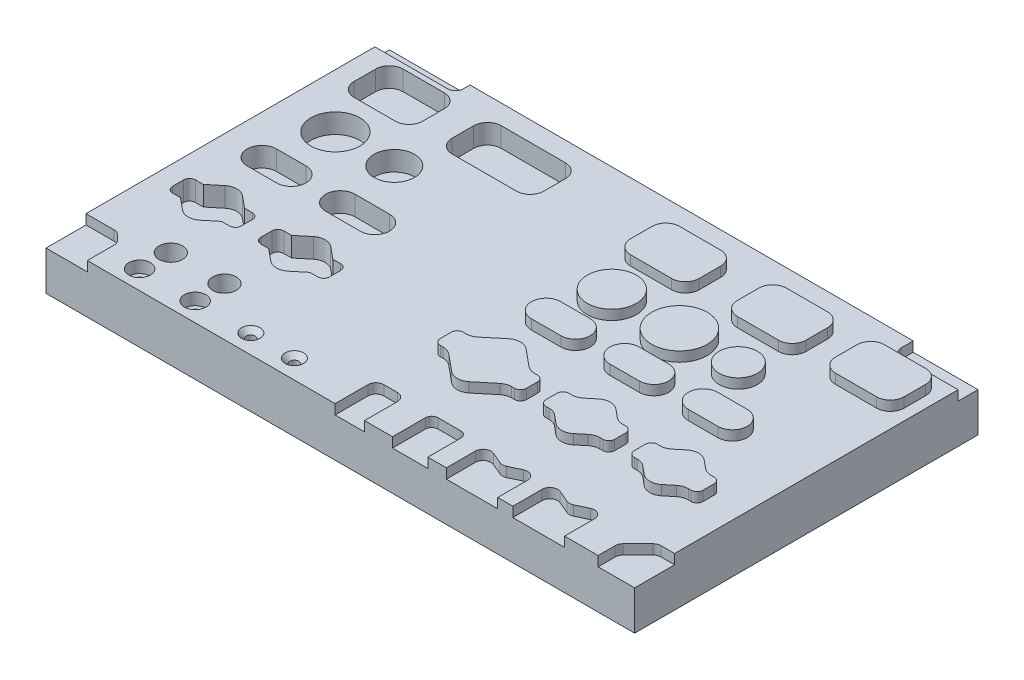
SolidWorks part; units mm, degrees
ref_plane "Front Plane" through (0, 0, 0) normal (0, 0, 1) x (1, 0, 0)
ref_plane "Top Plane" through (0, 0, 0) normal (0, 1, 0) x (1, 0, 0)
ref_plane "Right Plane" through (0, 0, 0) normal (1, 0, 0) x (0, 0, -1)
sketch "Sketch1" plane through (0, 0, 0) normal (0, 1, 0) x (1, 0, 0)
  line L1 (0, 0) -> (300, 0)
  line L2 (0, 0) -> (0, 175)
  line L3 (0, 175) -> (300, 175)
  line L4 (300, 0) -> (300, 175)
  dimension "D1" = 300
  dimension "D2" = 175
extrude "Boss-Extrude1" add sketch "Sketch1" against normal blind 25
sketch "Sketch2" plane through (0, 0, 0) normal (0, 1, 0) x (1, 0, 0)
  line L0 (0, 175) -> (0, 0) construction
  line L1 (27, 140) -> (48, 140)
  line L2 (20, 147) -> (20, 158)
  line L3 (27, 165) -> (48, 165)
  line L4 (55, 147) -> (55, 158)
  line L5 (300, 175) -> (0, 175) construction
  line L6 (89.9746, 138.8199) -> (122.7352, 138.8199)
  line L7 (82.9746, 145.8199) -> (82.9746, 156.8199)
  line L8 (89.9746, 163.8199) -> (122.7352, 163.8199)
  line L9 (129.7352, 145.8199) -> (129.7352, 156.8199)
  line L14 (37.5, 140) -> (37.5, 55.1696) construction
  line L15 (30, 90) -> (45, 90) construction
  line L16 (30, 97.5) -> (45, 97.5)
  line L17 (30, 82.5) -> (45, 82.5)
  line L18 (60, 90) -> (77.5906, 90) construction
  line L19 (60, 97.5) -> (77.5906, 97.5)
  line L20 (60, 82.5) -> (77.5906, 82.5)
  line L24 (33.0424, 76.426) -> (17, 63.1763)
  line L25 (17, 63.1763) -> (13, 63.1763)
  line L26 (10, 60.1763) -> (10, 54.5137)
  line L27 (10, 57.345) -> (37.5, 57.345) construction
  line L28 (65, 60.1763) -> (65, 54.5137)
  line L29 (58, 63.1763) -> (62, 63.1763)
  line L30 (41.9576, 76.426) -> (58, 63.1763)
  line L31 (41.9576, 38.2639) -> (58, 51.5137)
  line L32 (58, 51.5137) -> (62, 51.5137)
  line L33 (17, 51.5137) -> (13, 51.5137)
  line L34 (33.0424, 38.2639) -> (17, 51.5137)
  line L35 (68.0424, 68.1668) -> (62, 63.1763)
  line L36 (62, 63.1763) -> (58, 63.1763)
  line L37 (55, 60.1763) -> (55, 54.5137)
  line L38 (90, 60.1763) -> (90, 54.5137)
  line L39 (83, 63.1763) -> (87, 63.1763)
  line L40 (76.9576, 68.1668) -> (83, 63.1763)
  line L41 (76.9576, 46.5231) -> (83, 51.5137)
  line L42 (83, 51.5137) -> (87, 51.5137)
  line L43 (62, 51.5137) -> (58, 51.5137)
  line L44 (68.0424, 46.5231) -> (62, 51.5137)
  line L45 (55, 57.345) -> (72.5, 57.345) construction
  line L57 (161.8786, 135.9976) -> (182.8786, 135.9976)
  line L58 (154.8786, 142.9976) -> (154.8786, 153.9976)
  line L59 (161.8786, 160.9976) -> (182.8786, 160.9976)
  line L60 (189.8786, 142.9976) -> (189.8786, 153.9976)
  line L61 (216.3363, 135.9976) -> (237.3363, 135.9976)
  line L62 (209.3363, 142.9976) -> (209.3363, 153.9976)
  line L63 (216.3363, 160.9976) -> (237.3363, 160.9976)
  line L64 (244.3363, 142.9976) -> (244.3363, 153.9976)
  line L65 (266.3363, 135.9976) -> (287.3363, 135.9976)
  line L66 (259.3363, 142.9976) -> (259.3363, 153.9976)
  line L67 (266.3363, 160.9976) -> (287.3363, 160.9976)
  line L68 (294.3363, 142.9976) -> (294.3363, 153.9976)
  line L69 (172.3786, 135.9976) -> (172.3786, 51.1671) construction
  line L70 (164.8786, 90) -> (179.8786, 90) construction
  line L71 (164.8786, 97.5) -> (179.8786, 97.5)
  line L72 (164.8786, 82.5) -> (179.8786, 82.5)
  line L73 (204.8786, 90) -> (219.8786, 90) construction
  line L74 (204.8786, 97.5) -> (219.8786, 97.5)
  line L75 (204.8786, 82.5) -> (219.8786, 82.5)
  line L76 (244.8786, 90) -> (259.8786, 90) construction
  line L77 (244.8786, 97.5) -> (259.8786, 97.5)
  line L78 (244.8786, 82.5) -> (259.8786, 82.5)
  line L79 (167.921, 67.846) -> (157.421, 59.1738)
  line L80 (157.421, 59.1738) -> (153.421, 59.1738)
  line L81 (150.421, 56.1738) -> (150.421, 50.5112)
  line L82 (150.421, 53.3425) -> (172.3786, 53.3425) construction
  line L83 (194.3363, 56.1738) -> (194.3363, 50.5112)
  line L84 (187.3363, 59.1738) -> (191.3363, 59.1738)
  line L85 (176.8363, 67.846) -> (187.3363, 59.1738)
  line L86 (176.8363, 38.839) -> (187.3363, 47.5112)
  line L87 (187.3363, 47.5112) -> (191.3363, 47.5112)
  line L88 (157.421, 47.5112) -> (153.421, 47.5112)
  line L89 (167.921, 38.839) -> (157.421, 47.5112)
  line L90 (217.3786, 64.1644) -> (211.3363, 59.1738)
  line L91 (211.3363, 59.1738) -> (207.3363, 59.1738)
  line L92 (204.3363, 56.1738) -> (204.3363, 50.5112)
  line L93 (239.3363, 56.1738) -> (239.3363, 50.5112)
  line L94 (232.3363, 59.1738) -> (236.3363, 59.1738)
  line L95 (226.2939, 64.1644) -> (232.3363, 59.1738)
  line L96 (226.2939, 42.5207) -> (232.3363, 47.5112)
  line L97 (232.3363, 47.5112) -> (236.3363, 47.5112)
  line L98 (211.3363, 47.5112) -> (207.3363, 47.5112)
  line L99 (217.3786, 42.5207) -> (211.3363, 47.5112)
  line L100 (204.3363, 53.3425) -> (221.8363, 53.3425) construction
  line L101 (262.3786, 64.1644) -> (256.3363, 59.1738)
  line L102 (256.3363, 59.1738) -> (252.3363, 59.1738)
  line L103 (249.3363, 56.1738) -> (249.3363, 50.5112)
  line L104 (284.3363, 56.1738) -> (284.3363, 50.5112)
  line L105 (277.3363, 59.1738) -> (281.3363, 59.1738)
  line L106 (271.2939, 64.1644) -> (277.3363, 59.1738)
  line L107 (271.2939, 42.5207) -> (277.3363, 47.5112)
  line L108 (277.3363, 47.5112) -> (281.3363, 47.5112)
  line L109 (256.3363, 47.5112) -> (252.3363, 47.5112)
  line L110 (262.3786, 42.5207) -> (256.3363, 47.5112)
  line L111 (249.3363, 53.3425) -> (266.8363, 53.3425) construction
  arc A0 (27, 140) -> (20, 147) centre (27, 147) cw
  arc A1 (48, 140) -> (55, 147) centre (48, 147) ccw
  arc A2 (48, 165) -> (55, 158) centre (48, 158) cw
  arc A3 (20, 158) -> (27, 165) centre (27, 158) cw
  arc A4 (89.9746, 138.8199) -> (82.9746, 145.8199) centre (89.9746, 145.8199) cw
  arc A5 (122.7352, 138.8199) -> (129.7352, 145.8199) centre (122.7352, 145.8199) ccw
  arc A6 (122.7352, 163.8199) -> (129.7352, 156.8199) centre (122.7352, 156.8199) cw
  arc A7 (82.9746, 156.8199) -> (89.9746, 163.8199) centre (89.9746, 156.8199) cw
  circle A12 centre (37.5, 120) radius 12.5
  circle A13 centre (57.5, 120) radius 10.2904
  arc A15 (30, 97.5) -> (30, 82.5) centre (30, 90) ccw
  arc A16 (45, 82.5) -> (45, 97.5) centre (45, 90) ccw
  arc A17 (60, 97.5) -> (60, 82.5) centre (60, 90) ccw
  arc A18 (77.5906, 82.5) -> (77.5906, 97.5) centre (77.5906, 90) ccw
  arc A21 (41.9576, 38.2639) -> (33.0424, 38.2639) centre (37.5, 43.6611) cw
  arc A22 (33.0424, 76.426) -> (41.9576, 76.426) centre (37.5, 71.0289) cw
  arc A23 (13, 63.1763) -> (10, 60.1763) centre (13, 60.1763) ccw
  arc A24 (13, 51.5137) -> (10, 54.5137) centre (13, 54.5137) cw
  arc A25 (62, 51.5137) -> (65, 54.5137) centre (62, 54.5137) ccw
  arc A26 (65, 60.1763) -> (62, 63.1763) centre (62, 60.1763) ccw
  arc A27 (76.9576, 46.5231) -> (68.0424, 46.5231) centre (72.5, 51.9203) cw
  arc A28 (68.0424, 68.1668) -> (76.9576, 68.1668) centre (72.5, 62.7696) cw
  arc A29 (58, 63.1763) -> (55, 60.1763) centre (58, 60.1763) ccw
  arc A30 (58, 51.5137) -> (55, 54.5137) centre (58, 54.5137) cw
  arc A31 (87, 51.5137) -> (90, 54.5137) centre (87, 54.5137) ccw
  arc A32 (90, 60.1763) -> (87, 63.1763) centre (87, 60.1763) ccw
  arc A39 (161.8786, 135.9976) -> (154.8786, 142.9976) centre (161.8786, 142.9976) cw
  arc A40 (182.8786, 135.9976) -> (189.8786, 142.9976) centre (182.8786, 142.9976) ccw
  arc A41 (182.8786, 160.9976) -> (189.8786, 153.9976) centre (182.8786, 153.9976) cw
  arc A42 (154.8786, 153.9976) -> (161.8786, 160.9976) centre (161.8786, 153.9976) cw
  arc A43 (216.3363, 135.9976) -> (209.3363, 142.9976) centre (216.3363, 142.9976) cw
  arc A44 (237.3363, 135.9976) -> (244.3363, 142.9976) centre (237.3363, 142.9976) ccw
  arc A45 (237.3363, 160.9976) -> (244.3363, 153.9976) centre (237.3363, 153.9976) cw
  arc A46 (209.3363, 153.9976) -> (216.3363, 160.9976) centre (216.3363, 153.9976) cw
  arc A47 (266.3363, 135.9976) -> (259.3363, 142.9976) centre (266.3363, 142.9976) cw
  arc A48 (287.3363, 135.9976) -> (294.3363, 142.9976) centre (287.3363, 142.9976) ccw
  arc A49 (287.3363, 160.9976) -> (294.3363, 153.9976) centre (287.3363, 153.9976) cw
  arc A50 (259.3363, 153.9976) -> (266.3363, 160.9976) centre (266.3363, 153.9976) cw
  circle A51 centre (172.3786, 115.9976) radius 12.5
  circle A52 centre (206.8363, 115.9976) radius 12.5
  circle A53 centre (236.8363, 115.9976) radius 12.5
  arc A54 (164.8786, 97.5) -> (164.8786, 82.5) centre (164.8786, 90) ccw
  arc A55 (179.8786, 82.5) -> (179.8786, 97.5) centre (179.8786, 90) ccw
  arc A56 (204.8786, 97.5) -> (204.8786, 82.5) centre (204.8786, 90) ccw
  arc A57 (219.8786, 82.5) -> (219.8786, 97.5) centre (219.8786, 90) ccw
  arc A58 (244.8786, 97.5) -> (244.8786, 82.5) centre (244.8786, 90) ccw
  arc A59 (259.8786, 82.5) -> (259.8786, 97.5) centre (259.8786, 90) ccw
  arc A60 (176.8363, 38.839) -> (167.921, 38.839) centre (172.3786, 44.2362) cw
  arc A61 (167.921, 67.846) -> (176.8363, 67.846) centre (172.3786, 62.4489) cw
  arc A62 (153.421, 59.1738) -> (150.421, 56.1738) centre (153.421, 56.1738) ccw
  arc A63 (153.421, 47.5112) -> (150.421, 50.5112) centre (153.421, 50.5112) cw
  arc A64 (191.3363, 47.5112) -> (194.3363, 50.5112) centre (191.3363, 50.5112) ccw
  arc A65 (194.3363, 56.1738) -> (191.3363, 59.1738) centre (191.3363, 56.1738) ccw
  arc A66 (226.2939, 42.5207) -> (217.3786, 42.5207) centre (221.8363, 47.9179) cw
  arc A67 (217.3786, 64.1644) -> (226.2939, 64.1644) centre (221.8363, 58.7672) cw
  arc A68 (207.3363, 59.1738) -> (204.3363, 56.1738) centre (207.3363, 56.1738) ccw
  arc A69 (207.3363, 47.5112) -> (204.3363, 50.5112) centre (207.3363, 50.5112) cw
  arc A70 (236.3363, 47.5112) -> (239.3363, 50.5112) centre (236.3363, 50.5112) ccw
  arc A71 (239.3363, 56.1738) -> (236.3363, 59.1738) centre (236.3363, 56.1738) ccw
  arc A72 (271.2939, 42.5207) -> (262.3786, 42.5207) centre (266.8363, 47.9179) cw
  arc A73 (262.3786, 64.1644) -> (271.2939, 64.1644) centre (266.8363, 58.7672) cw
  arc A74 (252.3363, 59.1738) -> (249.3363, 56.1738) centre (252.3363, 56.1738) ccw
  arc A75 (252.3363, 47.5112) -> (249.3363, 50.5112) centre (252.3363, 50.5112) cw
  arc A76 (281.3363, 47.5112) -> (284.3363, 50.5112) centre (281.3363, 50.5112) ccw
  arc A77 (284.3363, 56.1738) -> (281.3363, 59.1738) centre (281.3363, 56.1738) ccw
  point P12 (55, 140)
  point P15 (55, 165)
  point P18 (20, 165)
  point P53 (37.5, 90)
  point P62 (68.7953, 90)
  point P83 (65, 57.345)
  point P87 (37.5, 34.5822)
  point P90 (37.5, 80.1077)
  point P93 (10, 63.1763)
  point P96 (10, 51.5137)
  point P99 (65, 51.5137)
  point P102 (65, 63.1763)
  point P116 (90, 57.345)
  point P199 (172.3786, 90)
  point P210 (212.3786, 90)
  point P217 (252.3786, 90)
  point P229 (194.3363, 53.3425)
  point P254 (239.3363, 53.3425)
  point P279 (284.3363, 53.3425)
  dimension "D5" = 7
  dimension "D7" = 25
  dimension "D11" = 7.5
  dimension "D14" = 7
  dimension "D15" = 3
  dimension "D17" = 7
  dimension "D18" = 25
  dimension "D20" = 7.5
  dimension "D22" = 7
  dimension "D23" = 3
  dimension "D1" = 20
  dimension "D2" = 10
  dimension "D3" = 35
  dimension "D4" = 25
  dimension "D8" = 55
  dimension "D10" = 15
  dimension "D12" = 30
  dimension "D19" = 15
  dimension "D21" = 3
sketch "Sketch6" plane through (0, 0, 0) normal (0, 1, 0) x (1, 0, 0)
  line L2 (35, 97.5) -> (20, 97.5)
  line L3 (20, 82.5) -> (35, 82.5)
  line L4 (10, 158) -> (10, 147)
  line L5 (17, 140) -> (38, 140)
  line L6 (45, 147) -> (45, 158)
  line L7 (38, 165) -> (17, 165)
  line L8 (10, 158) -> (10, 147)
  line L9 (17, 140) -> (38, 140)
  line L10 (45, 147) -> (45, 158)
  line L11 (38, 165) -> (17, 165)
  line L20 (99.7606, 165) -> (67, 165)
  line L21 (106.7606, 147) -> (106.7606, 158)
  line L22 (67, 140) -> (99.7606, 140)
  line L23 (60, 158) -> (60, 147)
  line L24 (99.7606, 165) -> (67, 165)
  line L25 (106.7606, 147) -> (106.7606, 158)
  line L26 (67, 140) -> (99.7606, 140)
  line L27 (60, 158) -> (60, 147)
  line L28 (35, 97.5) -> (20, 97.5)
  line L29 (20, 82.5) -> (35, 82.5)
  line L34 (60, 82.5) -> (77.5906, 82.5)
  line L35 (77.5906, 97.5) -> (60, 97.5)
  line L36 (60, 82.5) -> (77.5906, 82.5)
  line L37 (77.5906, 97.5) -> (60, 97.5)
  line L46 (45, 54.5137) -> (45, 60.1763)
  line L47 (38, 51.5137) -> (42, 51.5137)
  line L48 (31.9576, 46.5231) -> (38, 51.5137)
  line L49 (17, 51.5137) -> (23.0424, 46.5231)
  line L50 (13, 51.5137) -> (17, 51.5137)
  line L51 (10, 60.1763) -> (10, 54.5137)
  line L52 (17, 63.1763) -> (13, 63.1763)
  line L53 (23.0424, 68.1668) -> (17, 63.1763)
  line L54 (38, 63.1763) -> (31.9576, 68.1668)
  line L55 (42, 63.1763) -> (38, 63.1763)
  line L56 (45, 54.5137) -> (45, 60.1763)
  line L57 (38, 51.5137) -> (42, 51.5137)
  line L58 (31.9576, 46.5231) -> (38, 51.5137)
  line L59 (17, 51.5137) -> (23.0424, 46.5231)
  line L60 (13, 51.5137) -> (17, 51.5137)
  line L61 (10, 60.1763) -> (10, 54.5137)
  line L62 (17, 63.1763) -> (13, 63.1763)
  line L63 (23.0424, 68.1668) -> (17, 63.1763)
  line L64 (38, 63.1763) -> (31.9576, 68.1668)
  line L65 (42, 63.1763) -> (38, 63.1763)
  line L66 (90, 54.5137) -> (90, 60.1763)
  line L67 (83, 51.5137) -> (87, 51.5137)
  line L68 (76.9576, 46.5231) -> (83, 51.5137)
  line L69 (62, 51.5137) -> (68.0424, 46.5231)
  line L70 (58, 51.5137) -> (62, 51.5137)
  line L71 (55, 60.1763) -> (55, 54.5137)
  line L72 (62, 63.1763) -> (58, 63.1763)
  line L73 (68.0424, 68.1668) -> (62, 63.1763)
  line L74 (83, 63.1763) -> (76.9576, 68.1668)
  line L75 (87, 63.1763) -> (83, 63.1763)
  line L76 (90, 54.5137) -> (90, 60.1763)
  line L77 (83, 51.5137) -> (87, 51.5137)
  line L78 (76.9576, 46.5231) -> (83, 51.5137)
  line L79 (62, 51.5137) -> (68.0424, 46.5231)
  line L80 (58, 51.5137) -> (62, 51.5137)
  line L81 (55, 60.1763) -> (55, 54.5137)
  line L82 (62, 63.1763) -> (58, 63.1763)
  line L83 (68.0424, 68.1668) -> (62, 63.1763)
  line L84 (83, 63.1763) -> (76.9576, 68.1668)
  line L85 (87, 63.1763) -> (83, 63.1763)
  circle A1 centre (27.5, 120) radius 12.5
  circle A2 centre (27.5, 120) radius 12.5
  circle A5 centre (57.5, 120) radius 10.2904
  arc A6 (10, 147) -> (17, 140) centre (17, 147) ccw
  arc A7 (38, 140) -> (45, 147) centre (38, 147) ccw
  arc A8 (45, 158) -> (38, 165) centre (38, 158) ccw
  arc A9 (17, 165) -> (10, 158) centre (17, 158) ccw
  arc A10 (10, 147) -> (17, 140) centre (17, 147) ccw
  arc A11 (38, 140) -> (45, 147) centre (38, 147) ccw
  arc A12 (45, 158) -> (38, 165) centre (38, 158) ccw
  arc A13 (17, 165) -> (10, 158) centre (17, 158) ccw
  arc A22 (106.7606, 158) -> (99.7606, 165) centre (99.7606, 158) ccw
  arc A23 (99.7606, 140) -> (106.7606, 147) centre (99.7606, 147) ccw
  arc A24 (60, 147) -> (67, 140) centre (67, 147) ccw
  arc A25 (67, 165) -> (60, 158) centre (67, 158) ccw
  arc A26 (106.7606, 158) -> (99.7606, 165) centre (99.7606, 158) ccw
  arc A27 (99.7606, 140) -> (106.7606, 147) centre (99.7606, 147) ccw
  arc A28 (60, 147) -> (67, 140) centre (67, 147) ccw
  arc A29 (67, 165) -> (60, 158) centre (67, 158) ccw
  circle A30 centre (57.5, 120) radius 10.2904
  arc A32 (35, 82.5) -> (35, 97.5) centre (35, 90) ccw
  arc A33 (20, 97.5) -> (20, 82.5) centre (20, 90) ccw
  arc A34 (35, 82.5) -> (35, 97.5) centre (35, 90) ccw
  arc A35 (20, 97.5) -> (20, 82.5) centre (20, 90) ccw
  arc A40 (77.5906, 82.5) -> (77.5906, 97.5) centre (77.5906, 90) ccw
  arc A41 (60, 97.5) -> (60, 82.5) centre (60, 90) ccw
  arc A42 (77.5906, 82.5) -> (77.5906, 97.5) centre (77.5906, 90) ccw
  arc A43 (60, 97.5) -> (60, 82.5) centre (60, 90) ccw
  arc A48 (42, 51.5137) -> (45, 54.5137) centre (42, 54.5137) ccw
  arc A49 (23.0424, 46.5231) -> (31.9576, 46.5231) centre (27.5, 51.9203) ccw
  arc A50 (10, 54.5137) -> (13, 51.5137) centre (13, 54.5137) ccw
  arc A51 (13, 63.1763) -> (10, 60.1763) centre (13, 60.1763) ccw
  arc A52 (31.9576, 68.1668) -> (23.0424, 68.1668) centre (27.5, 62.7696) ccw
  arc A53 (45, 60.1763) -> (42, 63.1763) centre (42, 60.1763) ccw
  arc A54 (42, 51.5137) -> (45, 54.5137) centre (42, 54.5137) ccw
  arc A55 (23.0424, 46.5231) -> (31.9576, 46.5231) centre (27.5, 51.9203) ccw
  arc A56 (10, 54.5137) -> (13, 51.5137) centre (13, 54.5137) ccw
  arc A57 (13, 63.1763) -> (10, 60.1763) centre (13, 60.1763) ccw
  arc A58 (31.9576, 68.1668) -> (23.0424, 68.1668) centre (27.5, 62.7696) ccw
  arc A59 (45, 60.1763) -> (42, 63.1763) centre (42, 60.1763) ccw
  arc A60 (87, 51.5137) -> (90, 54.5137) centre (87, 54.5137) ccw
  arc A61 (68.0424, 46.5231) -> (76.9576, 46.5231) centre (72.5, 51.9203) ccw
  arc A62 (55, 54.5137) -> (58, 51.5137) centre (58, 54.5137) ccw
  arc A63 (58, 63.1763) -> (55, 60.1763) centre (58, 60.1763) ccw
  arc A64 (76.9576, 68.1668) -> (68.0424, 68.1668) centre (72.5, 62.7696) ccw
  arc A65 (90, 60.1763) -> (87, 63.1763) centre (87, 60.1763) ccw
  arc A66 (87, 51.5137) -> (90, 54.5137) centre (87, 54.5137) ccw
  arc A67 (68.0424, 46.5231) -> (76.9576, 46.5231) centre (72.5, 51.9203) ccw
  arc A68 (55, 54.5137) -> (58, 51.5137) centre (58, 54.5137) ccw
  arc A69 (58, 63.1763) -> (55, 60.1763) centre (58, 60.1763) ccw
  arc A70 (76.9576, 68.1668) -> (68.0424, 68.1668) centre (72.5, 62.7696) ccw
  arc A71 (90, 60.1763) -> (87, 63.1763) centre (87, 60.1763) ccw
  dimension "D1" = 0
  dimension "D2" = 0
  dimension "D4" = 0
  dimension "D6" = 0
  dimension "D7" = 0
  dimension "D9" = 0
  dimension "D10" = 0
  dimension "D11" = 0
extrude "Cut-Extrude2" cut sketch "Sketch6" against normal blind 10
sketch "Sketch8" plane through (0, 0, 0) normal (0, 1, 0) x (1, 0, 0)
  line L38 (179.8786, 97.5) -> (164.8786, 97.5)
  line L39 (164.8786, 82.5) -> (179.8786, 82.5)
  line L40 (154.8786, 153.9976) -> (154.8786, 142.9976)
  line L41 (161.8786, 135.9976) -> (182.8786, 135.9976)
  line L42 (189.8786, 142.9976) -> (189.8786, 153.9976)
  line L43 (182.8786, 160.9976) -> (161.8786, 160.9976)
  line L44 (154.8786, 153.9976) -> (154.8786, 142.9976)
  line L45 (161.8786, 135.9976) -> (182.8786, 135.9976)
  line L106 (189.8786, 142.9976) -> (189.8786, 153.9976)
  line L107 (182.8786, 160.9976) -> (161.8786, 160.9976)
  line L108 (266.3363, 135.9976) -> (287.3363, 135.9976)
  line L109 (294.3363, 142.9976) -> (294.3363, 153.9976)
  line L110 (287.3363, 160.9976) -> (266.3363, 160.9976)
  line L111 (259.3363, 153.9976) -> (259.3363, 142.9976)
  line L112 (266.3363, 135.9976) -> (287.3363, 135.9976)
  line L113 (294.3363, 142.9976) -> (294.3363, 153.9976)
  line L114 (287.3363, 160.9976) -> (266.3363, 160.9976)
  line L115 (259.3363, 153.9976) -> (259.3363, 142.9976)
  line L116 (209.3363, 153.9976) -> (209.3363, 142.9976)
  line L117 (216.3363, 135.9976) -> (237.3363, 135.9976)
  line L118 (244.3363, 142.9976) -> (244.3363, 153.9976)
  line L119 (237.3363, 160.9976) -> (216.3363, 160.9976)
  line L120 (209.3363, 153.9976) -> (209.3363, 142.9976)
  line L121 (216.3363, 135.9976) -> (237.3363, 135.9976)
  line L122 (244.3363, 142.9976) -> (244.3363, 153.9976)
  line L123 (237.3363, 160.9976) -> (216.3363, 160.9976)
  line L124 (179.8786, 97.5) -> (164.8786, 97.5)
  line L125 (164.8786, 82.5) -> (179.8786, 82.5)
  line L126 (259.8786, 97.5) -> (244.8786, 97.5)
  line L127 (244.8786, 82.5) -> (259.8786, 82.5)
  line L128 (259.8786, 97.5) -> (244.8786, 97.5)
  line L129 (244.8786, 82.5) -> (259.8786, 82.5)
  line L130 (219.8786, 97.5) -> (204.8786, 97.5)
  line L131 (204.8786, 82.5) -> (219.8786, 82.5)
  line L132 (219.8786, 97.5) -> (204.8786, 97.5)
  line L133 (204.8786, 82.5) -> (219.8786, 82.5)
  line L142 (194.3363, 50.5112) -> (194.3363, 56.1738)
  line L143 (187.3363, 47.5112) -> (191.3363, 47.5112)
  line L144 (176.8363, 38.839) -> (187.3363, 47.5112)
  line L145 (157.421, 47.5112) -> (167.921, 38.839)
  line L146 (153.421, 47.5112) -> (157.421, 47.5112)
  line L147 (150.421, 56.1738) -> (150.421, 50.5112)
  line L148 (157.421, 59.1738) -> (153.421, 59.1738)
  line L149 (167.921, 67.846) -> (157.421, 59.1738)
  line L150 (187.3363, 59.1738) -> (176.8363, 67.846)
  line L151 (191.3363, 59.1738) -> (187.3363, 59.1738)
  line L152 (194.3363, 50.5112) -> (194.3363, 56.1738)
  line L153 (187.3363, 47.5112) -> (191.3363, 47.5112)
  line L154 (176.8363, 38.839) -> (187.3363, 47.5112)
  line L155 (157.421, 47.5112) -> (167.921, 38.839)
  line L156 (153.421, 47.5112) -> (157.421, 47.5112)
  line L157 (150.421, 56.1738) -> (150.421, 50.5112)
  line L158 (157.421, 59.1738) -> (153.421, 59.1738)
  line L159 (167.921, 67.846) -> (157.421, 59.1738)
  line L160 (187.3363, 59.1738) -> (176.8363, 67.846)
  line L161 (191.3363, 59.1738) -> (187.3363, 59.1738)
  line L162 (256.3363, 59.1738) -> (252.3363, 59.1738)
  line L163 (249.3363, 56.1738) -> (249.3363, 50.5112)
  line L164 (252.3363, 47.5112) -> (256.3363, 47.5112)
  line L165 (256.3363, 47.5112) -> (262.3786, 42.5207)
  line L166 (271.2939, 42.5207) -> (277.3363, 47.5112)
  line L167 (277.3363, 47.5112) -> (281.3363, 47.5112)
  line L168 (284.3363, 50.5112) -> (284.3363, 56.1738)
  line L169 (281.3363, 59.1738) -> (277.3363, 59.1738)
  line L170 (277.3363, 59.1738) -> (271.2939, 64.1644)
  line L171 (262.3786, 64.1644) -> (256.3363, 59.1738)
  line L172 (256.3363, 59.1738) -> (252.3363, 59.1738)
  line L173 (249.3363, 56.1738) -> (249.3363, 50.5112)
  line L174 (252.3363, 47.5112) -> (256.3363, 47.5112)
  line L175 (256.3363, 47.5112) -> (262.3786, 42.5207)
  line L176 (271.2939, 42.5207) -> (277.3363, 47.5112)
  line L177 (277.3363, 47.5112) -> (281.3363, 47.5112)
  line L178 (284.3363, 50.5112) -> (284.3363, 56.1738)
  line L179 (281.3363, 59.1738) -> (277.3363, 59.1738)
  line L180 (277.3363, 59.1738) -> (271.2939, 64.1644)
  line L181 (262.3786, 64.1644) -> (256.3363, 59.1738)
  line L182 (217.3786, 64.1644) -> (211.3363, 59.1738)
  line L183 (211.3363, 59.1738) -> (207.3363, 59.1738)
  line L184 (204.3363, 56.1738) -> (204.3363, 50.5112)
  line L185 (207.3363, 47.5112) -> (211.3363, 47.5112)
  line L186 (211.3363, 47.5112) -> (217.3786, 42.5207)
  line L187 (226.2939, 42.5207) -> (232.3363, 47.5112)
  line L188 (232.3363, 47.5112) -> (236.3363, 47.5112)
  line L189 (239.3363, 50.5112) -> (239.3363, 56.1738)
  line L190 (236.3363, 59.1738) -> (232.3363, 59.1738)
  line L191 (232.3363, 59.1738) -> (226.2939, 64.1644)
  line L192 (217.3786, 64.1644) -> (211.3363, 59.1738)
  line L193 (211.3363, 59.1738) -> (207.3363, 59.1738)
  line L194 (204.3363, 56.1738) -> (204.3363, 50.5112)
  line L195 (207.3363, 47.5112) -> (211.3363, 47.5112)
  line L196 (211.3363, 47.5112) -> (217.3786, 42.5207)
  line L197 (226.2939, 42.5207) -> (232.3363, 47.5112)
  line L198 (232.3363, 47.5112) -> (236.3363, 47.5112)
  line L199 (239.3363, 50.5112) -> (239.3363, 56.1738)
  line L200 (236.3363, 59.1738) -> (232.3363, 59.1738)
  line L201 (232.3363, 59.1738) -> (226.2939, 64.1644)
  circle A31 centre (172.3786, 115.9976) radius 12.5
  circle A44 centre (172.3786, 115.9976) radius 12.5
  circle A46 centre (236.8363, 115.9976) radius 9.7324
  arc A84 (154.8786, 142.9976) -> (161.8786, 135.9976) centre (161.8786, 142.9976) ccw
  arc A85 (182.8786, 135.9976) -> (189.8786, 142.9976) centre (182.8786, 142.9976) ccw
  arc A86 (189.8786, 153.9976) -> (182.8786, 160.9976) centre (182.8786, 153.9976) ccw
  arc A87 (161.8786, 160.9976) -> (154.8786, 153.9976) centre (161.8786, 153.9976) ccw
  arc A88 (154.8786, 142.9976) -> (161.8786, 135.9976) centre (161.8786, 142.9976) ccw
  arc A89 (182.8786, 135.9976) -> (189.8786, 142.9976) centre (182.8786, 142.9976) ccw
  arc A90 (189.8786, 153.9976) -> (182.8786, 160.9976) centre (182.8786, 153.9976) ccw
  arc A91 (161.8786, 160.9976) -> (154.8786, 153.9976) centre (161.8786, 153.9976) ccw
  arc A92 (287.3363, 135.9976) -> (294.3363, 142.9976) centre (287.3363, 142.9976) ccw
  arc A93 (294.3363, 153.9976) -> (287.3363, 160.9976) centre (287.3363, 153.9976) ccw
  arc A94 (266.3363, 160.9976) -> (259.3363, 153.9976) centre (266.3363, 153.9976) ccw
  arc A95 (259.3363, 142.9976) -> (266.3363, 135.9976) centre (266.3363, 142.9976) ccw
  arc A96 (287.3363, 135.9976) -> (294.3363, 142.9976) centre (287.3363, 142.9976) ccw
  arc A97 (294.3363, 153.9976) -> (287.3363, 160.9976) centre (287.3363, 153.9976) ccw
  arc A98 (266.3363, 160.9976) -> (259.3363, 153.9976) centre (266.3363, 153.9976) ccw
  arc A99 (259.3363, 142.9976) -> (266.3363, 135.9976) centre (266.3363, 142.9976) ccw
  arc A100 (209.3363, 142.9976) -> (216.3363, 135.9976) centre (216.3363, 142.9976) ccw
  arc A101 (237.3363, 135.9976) -> (244.3363, 142.9976) centre (237.3363, 142.9976) ccw
  arc A102 (244.3363, 153.9976) -> (237.3363, 160.9976) centre (237.3363, 153.9976) ccw
  arc A103 (216.3363, 160.9976) -> (209.3363, 153.9976) centre (216.3363, 153.9976) ccw
  arc A104 (209.3363, 142.9976) -> (216.3363, 135.9976) centre (216.3363, 142.9976) ccw
  arc A105 (237.3363, 135.9976) -> (244.3363, 142.9976) centre (237.3363, 142.9976) ccw
  arc A106 (244.3363, 153.9976) -> (237.3363, 160.9976) centre (237.3363, 153.9976) ccw
  arc A107 (216.3363, 160.9976) -> (209.3363, 153.9976) centre (216.3363, 153.9976) ccw
  circle A108 centre (206.8363, 115.9976) radius 14.1618
  arc A110 (179.8786, 82.5) -> (179.8786, 97.5) centre (179.8786, 90) ccw
  arc A111 (164.8786, 97.5) -> (164.8786, 82.5) centre (164.8786, 90) ccw
  arc A112 (179.8786, 82.5) -> (179.8786, 97.5) centre (179.8786, 90) ccw
  arc A113 (164.8786, 97.5) -> (164.8786, 82.5) centre (164.8786, 90) ccw
  arc A114 (259.8786, 82.5) -> (259.8786, 97.5) centre (259.8786, 90) ccw
  arc A115 (244.8786, 97.5) -> (244.8786, 82.5) centre (244.8786, 90) ccw
  arc A116 (259.8786, 82.5) -> (259.8786, 97.5) centre (259.8786, 90) ccw
  arc A117 (244.8786, 97.5) -> (244.8786, 82.5) centre (244.8786, 90) ccw
  arc A118 (219.8786, 82.5) -> (219.8786, 97.5) centre (219.8786, 90) ccw
  arc A119 (204.8786, 97.5) -> (204.8786, 82.5) centre (204.8786, 90) ccw
  arc A120 (219.8786, 82.5) -> (219.8786, 97.5) centre (219.8786, 90) ccw
  arc A121 (204.8786, 97.5) -> (204.8786, 82.5) centre (204.8786, 90) ccw
  arc A126 (191.3363, 47.5112) -> (194.3363, 50.5112) centre (191.3363, 50.5112) ccw
  arc A127 (167.921, 38.839) -> (176.8363, 38.839) centre (172.3786, 44.2362) ccw
  arc A128 (150.421, 50.5112) -> (153.421, 47.5112) centre (153.421, 50.5112) ccw
  arc A129 (153.421, 59.1738) -> (150.421, 56.1738) centre (153.421, 56.1738) ccw
  arc A130 (176.8363, 67.846) -> (167.921, 67.846) centre (172.3786, 62.4489) ccw
  arc A131 (194.3363, 56.1738) -> (191.3363, 59.1738) centre (191.3363, 56.1738) ccw
  arc A132 (191.3363, 47.5112) -> (194.3363, 50.5112) centre (191.3363, 50.5112) ccw
  arc A133 (167.921, 38.839) -> (176.8363, 38.839) centre (172.3786, 44.2362) ccw
  arc A134 (150.421, 50.5112) -> (153.421, 47.5112) centre (153.421, 50.5112) ccw
  arc A135 (153.421, 59.1738) -> (150.421, 56.1738) centre (153.421, 56.1738) ccw
  arc A136 (176.8363, 67.846) -> (167.921, 67.846) centre (172.3786, 62.4489) ccw
  arc A137 (194.3363, 56.1738) -> (191.3363, 59.1738) centre (191.3363, 56.1738) ccw
  arc A138 (252.3363, 59.1738) -> (249.3363, 56.1738) centre (252.3363, 56.1738) ccw
  arc A139 (249.3363, 50.5112) -> (252.3363, 47.5112) centre (252.3363, 50.5112) ccw
  arc A140 (262.3786, 42.5207) -> (271.2939, 42.5207) centre (266.8363, 47.9179) ccw
  arc A141 (281.3363, 47.5112) -> (284.3363, 50.5112) centre (281.3363, 50.5112) ccw
  arc A142 (284.3363, 56.1738) -> (281.3363, 59.1738) centre (281.3363, 56.1738) ccw
  arc A143 (271.2939, 64.1644) -> (262.3786, 64.1644) centre (266.8363, 58.7672) ccw
  arc A144 (252.3363, 59.1738) -> (249.3363, 56.1738) centre (252.3363, 56.1738) ccw
  arc A145 (249.3363, 50.5112) -> (252.3363, 47.5112) centre (252.3363, 50.5112) ccw
  arc A146 (262.3786, 42.5207) -> (271.2939, 42.5207) centre (266.8363, 47.9179) ccw
  arc A147 (281.3363, 47.5112) -> (284.3363, 50.5112) centre (281.3363, 50.5112) ccw
  arc A148 (284.3363, 56.1738) -> (281.3363, 59.1738) centre (281.3363, 56.1738) ccw
  arc A149 (271.2939, 64.1644) -> (262.3786, 64.1644) centre (266.8363, 58.7672) ccw
  arc A150 (207.3363, 59.1738) -> (204.3363, 56.1738) centre (207.3363, 56.1738) ccw
  arc A151 (204.3363, 50.5112) -> (207.3363, 47.5112) centre (207.3363, 50.5112) ccw
  arc A152 (217.3786, 42.5207) -> (226.2939, 42.5207) centre (221.8363, 47.9179) ccw
  arc A153 (236.3363, 47.5112) -> (239.3363, 50.5112) centre (236.3363, 50.5112) ccw
  arc A154 (239.3363, 56.1738) -> (236.3363, 59.1738) centre (236.3363, 56.1738) ccw
  arc A155 (226.2939, 64.1644) -> (217.3786, 64.1644) centre (221.8363, 58.7672) ccw
  arc A156 (207.3363, 59.1738) -> (204.3363, 56.1738) centre (207.3363, 56.1738) ccw
  arc A157 (204.3363, 50.5112) -> (207.3363, 47.5112) centre (207.3363, 50.5112) ccw
  arc A158 (217.3786, 42.5207) -> (226.2939, 42.5207) centre (221.8363, 47.9179) ccw
  arc A159 (236.3363, 47.5112) -> (239.3363, 50.5112) centre (236.3363, 50.5112) ccw
  arc A160 (239.3363, 56.1738) -> (236.3363, 59.1738) centre (236.3363, 56.1738) ccw
  arc A161 (226.2939, 64.1644) -> (217.3786, 64.1644) centre (221.8363, 58.7672) ccw
  dimension "D13" = 0
  dimension "D14" = 0
  dimension "D15" = 0
  dimension "D16" = 0
  dimension "D19" = 0
  dimension "D20" = 0
  dimension "D21" = 0
  dimension "D22" = 0
  dimension "D23" = 0
  dimension "D24" = 0
extrude "Boss-Extrude2" add sketch "Sketch8" along normal blind 5
fillet "Fillet1" radius 7 12 edges at (277.3363, 2.5, -59.1738) (256.3363, 2.5, -59.1738) (232.3363, 2.5, -59.1738) (211.3363, 2.5, -59.1738) (187.3363, 2.5, -59.1738) (157.421, 2.5, -59.1738) (277.3363, 2.5, -47.5112) (256.3363, 2.5, -47.5112) (232.3363, 2.5, -47.5112) (211.3363, 2.5, -47.5112) (157.421, 2.5, -47.5112) (187.3363, 2.5, -47.5112)
hole_wizard "Ø12.0mm Dowel Hole1" positions "Sketch9" profile "Sketch11" hole size "Ø12.0" standard "ANSI Metric"
sketch "Sketch9" plane through (0, 0, 0) normal (0, 1, 0) x (1, 0, 0)
  point P0 (38.8502, 24.7455)
  point P2 (66.1786, 24.7455)
sketch "Sketch11" plane through (38.8502, 0, -24.7455) normal (1, 0, 0) x (0, 0, 1)
  line L0 (0, 0) -> (0, 18.6052)
  line L1 (0, 18.6052) -> (6, 15)
  line L2 (6, 15) -> (6, 0)
  line L5 (6, 0) -> (0, 0)
  line L10 (0, 18.6052) -> (-6, 15) construction
  line L11 (0, -6.35) -> (0, 107.95) construction
  dimension "Hole Dia." = 12
  dimension "Hole Depth" = 15
  dimension "Drill Angle" = 118
hole_wizard "CBORE for M6 SHCS1" positions "Sketch14" profile "Sketch13" counterbore size "M6" standard "ANSI Metric"
sketch "Sketch14" plane through (0, 0, 0) normal (0, 1, 0) x (1, 0, 0)
  point P0 (38.0313, 9.6751)
  point P2 (66.348, 9.6751)
sketch "Sketch13" plane through (38.0313, 0, -9.6751) normal (1, 0, 0) x (0, 0, 1)
  line L0 (0, 0) -> (0, 16.9828)
  line L1 (0, 16.9828) -> (3.3, 15)
  line L2 (3.3, 15) -> (3.3, 6)
  line L3 (3.3, 6) -> (5.5, 6)
  line L4 (5.5, 6) -> (5.5, 0)
  line L5 (5.5, 0) -> (0, 0)
  line L10 (0, 16.9828) -> (-3.3, 15) construction
  line L11 (0, -6.35) -> (0, 107.95) construction
  dimension "Hole Dia." = 6.6
  dimension "Hole Depth" = 15
  dimension "C'Bore Dia." = 11
  dimension "C'Bore Depth" = 6
  dimension "Drill Angle" = 118
hole_wizard "CSK for M4 Flat Head Machine Screw1" positions "Sketch17" profile "Sketch16" countersink size "M4" standard "ANSI Metric"
sketch "Sketch17" plane through (0, 0, 0) normal (0, 1, 0) x (1, 0, 0)
  point P0 (116.904, 9.6751)
  point P2 (94.7038, 9.6751)
sketch "Sketch16" plane through (116.904, 0, -9.6751) normal (1, 0, 0) x (0, 0, 1)
  line L0 (0, 0) -> (0, 16.3519)
  line L1 (0, 16.3519) -> (2.25, 15)
  line L2 (2.25, 15) -> (2.25, 2.45)
  line L3 (2.25, 2.45) -> (4.7, 0)
  line L5 (4.7, 0) -> (0, 0)
  line L6 (-2.25, 2.45) -> (-4.7, 0) construction
  line L10 (0, 16.3519) -> (-2.25, 15) construction
  line L11 (0, -6.35) -> (0, 107.95) construction
  dimension "Hole Dia." = 4.5
  dimension "Hole Depth" = 15
  dimension "Near C'Sink Dia." = 9.4
  dimension "Near C'Sink Angle" = 90
  dimension "Drill Angle" = 118
sketch "Sketch18" plane through (0, 0, 0) normal (0, 1, 0) x (1, 0, 0)
  line L0 (0, 0) -> (300, 0) construction
  line L1 (147.3421, 0) -> (162.3421, 0)
  line L2 (147.3421, 0) -> (147.3421, 16.8019)
  line L3 (151.3421, 20.8019) -> (158.3421, 20.8019)
  line L4 (162.3421, 0) -> (162.3421, 16.8019)
  line L5 (176.5953, 0) -> (194.5953, 0)
  line L6 (176.5953, 0) -> (176.5953, 16.8019)
  line L7 (179.7933, 20) -> (191.3972, 20)
  line L8 (194.5953, 0) -> (194.5953, 16.8019)
  line L9 (209.5919, 18.4547) -> (215.4666, 15.973)
  line L10 (204.0353, 0) -> (230.2059, 0)
  line L11 (204.0353, 0) -> (204.0353, 14.77)
  line L12 (218.7419, 16.0459) -> (224.4871, 18.7798)
  line L13 (230.2059, 0) -> (230.2059, 15.1679)
  line L14 (217.1206, 0) -> (217.1206, 24.9304) construction
  line L15 (243.4707, 18.583) -> (249.5382, 16.02)
  line L16 (237.9142, 0) -> (264.2775, 0)
  line L17 (237.9142, 0) -> (237.9142, 14.8983)
  line L18 (252.8135, 16.0928) -> (258.5587, 18.8267)
  line L19 (264.2775, 0) -> (264.2775, 15.2148)
  line L20 (251.0958, 0) -> (251.0958, 24.9773) construction
  arc A0 (147.3421, 16.8019) -> (151.3421, 20.8019) centre (151.3421, 16.8019) cw
  arc A1 (158.3421, 20.8019) -> (162.3421, 16.8019) centre (158.3421, 16.8019) cw
  arc A2 (176.5953, 16.8019) -> (179.7933, 20) centre (179.7933, 16.8019) cw
  arc A3 (191.3972, 20) -> (194.5953, 16.8019) centre (191.3972, 16.8019) cw
  arc A4 (230.2059, 15.1679) -> (224.4871, 18.7798) centre (226.2059, 15.1679) ccw
  arc A5 (204.0353, 14.77) -> (209.5919, 18.4547) centre (208.0353, 14.77) cw
  arc A6 (215.4666, 15.973) -> (218.7419, 16.0459) centre (217.0231, 19.6578) ccw
  arc A7 (264.2775, 15.2148) -> (258.5587, 18.8267) centre (260.2775, 15.2148) ccw
  arc A8 (237.9142, 14.8983) -> (243.4707, 18.583) centre (241.9142, 14.8983) cw
  arc A9 (249.5382, 16.02) -> (252.8135, 16.0928) centre (251.0948, 19.7047) ccw
  point P32 (217.1206, 15.2743)
  dimension "D1" = 4
  dimension "D4" = 4
  dimension "D5" = 4
  dimension "D2" = 20
  dimension "D3" = 18
extrude "Cut-Extrude3" cut sketch "Sketch18" against normal blind 5
sketch "Sketch21" plane through (0, 0, 0) normal (0, 1, 0) x (1, 0, 0)
  line L0 (300, 0) -> (300, 175) construction
  line L1 (300, 164.8939) -> (270.9846, 164.8939)
  line L2 (300, 164.8939) -> (300, 175)
  line L3 (300, 175) -> (266.9846, 175)
  line L4 (266.9846, 168.8939) -> (266.9846, 175)
  line L5 (300, 175) -> (0, 175) construction
  line L6 (290.2231, 19.1984) -> (282.5662, 11.5415)
  line L7 (0, 175) -> (41.084, 175)
  line L8 (0, 175) -> (0, 167.6184)
  line L9 (0, 167.6184) -> (37.084, 167.6184)
  line L10 (41.084, 175) -> (41.084, 171.6184)
  line L11 (300, 0) -> (281.3947, 0)
  line L12 (300, 0) -> (300, 20.37)
  line L13 (300, 20.37) -> (293.0515, 20.37)
  line L14 (281.3947, 0) -> (281.3947, 8.7131)
  line L15 (17.2189, 19.1984) -> (19.8757, 16.5415)
  line L16 (0, 0) -> (21.0473, 0)
  line L17 (0, 0) -> (0, 20.37)
  line L18 (0, 20.37) -> (14.3904, 20.37)
  line L19 (21.0473, 0) -> (21.0473, 13.7131)
  arc A0 (270.9846, 164.8939) -> (266.9846, 168.8939) centre (270.9846, 168.8939) cw
  arc A1 (37.084, 167.6184) -> (41.084, 171.6184) centre (37.084, 171.6184) ccw
  arc A2 (282.5662, 11.5415) -> (281.3947, 8.7131) centre (285.3947, 8.7131) ccw
  arc A3 (290.2231, 19.1984) -> (293.0515, 20.37) centre (293.0515, 16.37) cw
  arc A4 (19.8757, 16.5415) -> (21.0473, 13.7131) centre (17.0473, 13.7131) cw
  arc A5 (17.2189, 19.1984) -> (14.3904, 20.37) centre (14.3904, 16.37) ccw
  point P18 (281.3947, 20.37)
  point P26 (281.3947, 10.37)
  point P29 (291.3947, 20.37)
  point P31 (21.0473, 20.37)
  point P39 (21.0473, 15.37)
  point P42 (16.0473, 20.37)
  dimension "D1" = 4
  dimension "D2" = 4
  dimension "D3" = 4
  dimension "D4" = 4
extrude "Cut-Extrude6" cut sketch "Sketch21" against normal blind 5
